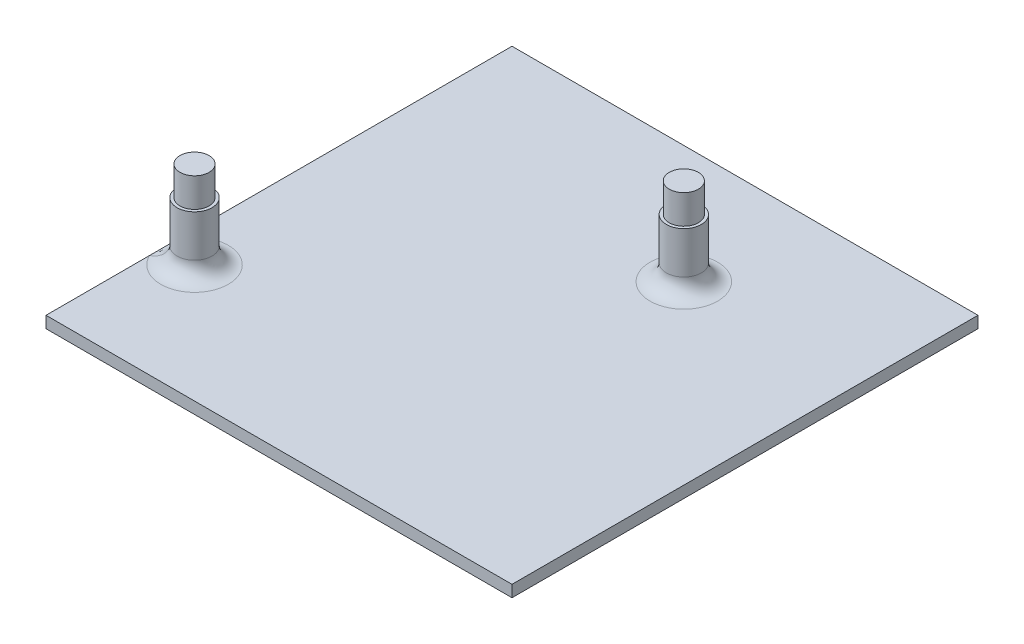
SolidWorks part; units mm, degrees
ref_plane "Front Plane" through (0, 0, 0) normal (0, 0, 1) x (1, 0, 0)
ref_plane "Top Plane" through (0, 0, 0) normal (0, 1, 0) x (1, 0, 0)
ref_plane "Right Plane" through (0, 0, 0) normal (1, 0, 0) x (0, 0, -1)
sketch "Sketch1" plane through (0, 0, 0) normal (0, 1, 0) x (1, 0, 0)
  line L0 (-27.5, 27.5) -> (-27.5, 40)
  line L1 (-27.5, 27.5) -> (27.5, 27.5)
  line L2 (-27.5, 27.5) -> (-27.5, -27.5)
  line L3 (-27.5, -27.5) -> (27.5, -27.5)
  line L4 (27.5, 27.5) -> (27.5, -27.5)
  line L5 (-27.5, 27.5) -> (27.5, -27.5) construction
  line L6 (-27.5, -27.5) -> (27.5, 27.5) construction
  line L7 (-27.5, 40) -> (52.5, 40)
  line L8 (-27.5, -27.5) -> (-27.5, -40)
  line L9 (-27.5, -40) -> (52.5, -40)
  line L10 (52.5, 40) -> (52.5, -40)
  line L11 (-27.5, -40) -> (-27.5, -27.5)
  circle A0 centre (22.25, -19.75) radius 2.5 construction
  circle A1 centre (-22.25, 22.25) radius 2.5 construction
  point P0 (0, 0)
  point P14 (52.5, 0)
  dimension "D5" = 5
  dimension "D1" = 55
  dimension "D2" = 5.25
  dimension "D3" = 19.75
  dimension "D4" = 5.25
  dimension "D6" = 80
  dimension "D7" = 80
extrude "Boss-Extrude1" add sketch "Sketch1" along normal blind 2 contours L10 L7 L0 L1 L4 L3 L8 L9 | L4 L1 L2 L3
sketch "Sketch2" plane through (0, 2, 0) normal (0, 1, 0) x (1, 0, 0)
  line L0 (-22.25, -19.75) -> (-22.25, -40) construction
  line L1 (-27.5, -40) -> (52.5, -40) construction
  line L2 (22.25, 19.75) -> (22.25, 40) construction
  line L3 (-27.5, 40) -> (52.5, 40) construction
  circle A0 centre (-22.25, -19.75) radius 3
  circle A1 centre (22.25, 19.75) radius 3
  dimension "D5" = 6
  dimension "D6" = 6
  dimension "D3" = 22.25
  dimension "D4" = 22.25
  dimension "D7" = 39.5
extrude "Boss-Extrude2" add sketch "Sketch2" along normal blind 10
fillet "Fillet1" radius 2.8 2 edges at (22.25, 2, -16.75) (-22.25, 2, 22.75)
sketch "Sketch3" plane through (0, 12, 0) normal (0, 1, 0) x (1, 0, 0)
  circle A0 centre (-22.25, -19.75) radius 2.5
  circle A1 centre (22.25, 19.75) radius 2.5
  dimension "D1" = 5
extrude "Boss-Extrude3" add sketch "Sketch3" along normal blind 5
